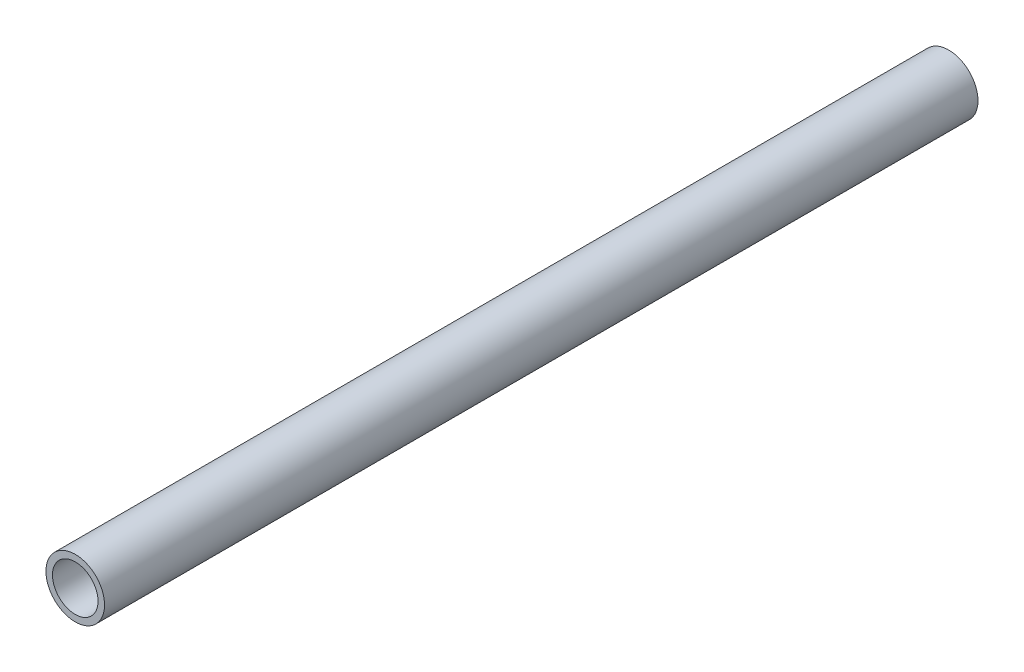
SolidWorks part; units mm, degrees
material "1.0553 (S355J0)"
ref_plane "Front Plane" through (0, 0, 0) normal (0, 0, 1) x (1, 0, 0)
ref_plane "Top Plane" through (0, 0, 0) normal (0, 1, 0) x (1, 0, 0)
ref_plane "Right Plane" through (0, 0, 0) normal (1, 0, 0) x (0, 0, -1)
sketch "Sketch1" plane through (0, 0, 0) normal (0, 0, 1) x (1, 0, 0)
  circle A0 centre (0, 0) radius 54
  circle A1 centre (0, 0) radius 42
  dimension "D1" = 108
  dimension "D2" = 12
extrude "Boss-Extrude1" add sketch "Sketch1" along normal mid plane 1610
